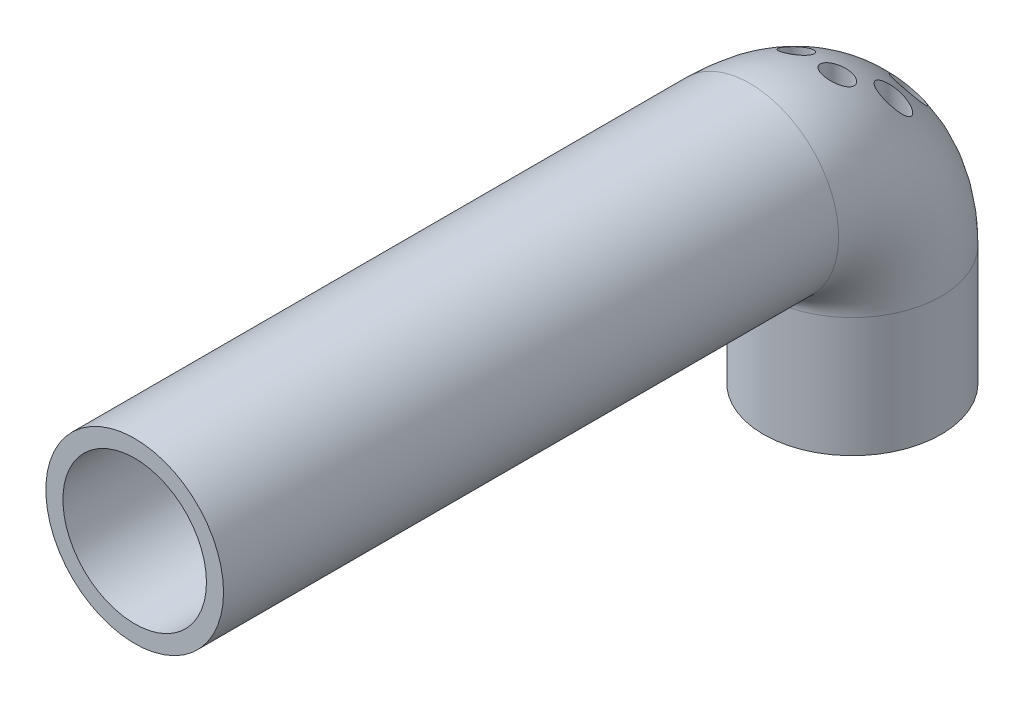
SolidWorks part; units mm, degrees
ref_plane "Front Plane" through (0, 0, 0) normal (0, 0, 1) x (1, 0, 0)
ref_plane "Top Plane" through (0, 0, 0) normal (0, 1, 0) x (1, 0, 0)
ref_plane "Right Plane" through (0, 0, 0) normal (1, 0, 0) x (0, 0, -1)
sketch "Sketch1" plane through (0, 0, 0) normal (0, 1, 0) x (1, 0, 0)
  line L0 (-21.2616, 0) -> (18.5116, 0) construction
  circle A1 centre (0, 0) radius 26
  dimension "D1" = 52
extrude "Boss-Extrude1" add sketch "Sketch1" along normal blind 5
sketch "Sketch8" plane through (0, 5, 0) normal (0, 1, 0) x (1, 0, 0)
  line L0 (6, 10.3923) -> (-6, -10.3923) construction
  line L2 (6, -10.3923) -> (-6, 10.3923) construction
  line L5 (0, 0) -> (0, 12) construction
  circle A0 centre (0, 0) radius 12 construction
  point P4 (-12, 0)
  point P6 (12, 0)
  point P9 (6, 10.3923)
  point P10 (-6, -10.3923)
  point P13 (6, -10.3923)
  point P14 (-6, 10.3923)
  dimension "D1" = 24
  dimension "D2" = 30
  dimension "D3" = 30
hole_wizard "CSK for M4 Flat Head Machine Screw2" positions "Sketch8" profile "Sketch9" countersink size "M4" standard "ANSI Metric" end condition through all
sketch "Sketch9" plane through (-6, 5, -10.3923) normal (1, 0, 0) x (0, 0, 1)
  line L0 (0, 0) -> (0, 5)
  line L1 (0, 5) -> (2.25, 5)
  line L2 (2.25, 5) -> (2.25, 1.75)
  line L3 (2.25, 1.75) -> (4, 0)
  line L5 (4, 0) -> (0, 0)
  line L6 (-2.25, 1.75) -> (-4, 0) construction
  line L11 (0, -6.35) -> (0, 107.95) construction
  dimension "Thru Hole Dia." = 4.5
  dimension "Thru Hole Depth" = 5
  dimension "Near C'Sink Dia." = 8
  dimension "Near C'Sink Angle" = 90
sketch "Sketch10" plane through (0, 0, 0) normal (1, 0, 0) x (0, 0, -1)
  line L0 (0, 5) -> (0, 35)
  line L1 (26, 5) -> (-26, 5) construction
  line L2 (-60, 65) -> (-30, 65)
  arc A0 (-30, 65) -> (0, 35) centre (-30, 35) cw
  dimension "D1" = 30
  dimension "D2" = 30
  dimension "D3" = 30
  dimension "D4" = 30
sketch "Sketch11" plane through (0, 5, 0) normal (0, 1, 0) x (1, 0, 0)
  circle A0 centre (0, 0) radius 21
  circle A1 centre (0, 0) radius 26
  circle A2 centre (0, 0) radius 26
  dimension "D1" = 0
  dimension "D2" = 5
sweep "Sweep3" add profiles "Sketch11" path "Sketch10"
ref_plane "Plane1" through (0, 39, 0) normal (0, -1, 0) x (-1, 0, 0)
sketch "Sketch13" plane through (0, 39, 0) normal (0, -1, 0) x (-1, 0, 0)
  circle A0 centre (-6, 10.3923) radius 2.25 construction
  circle A1 centre (-6, 10.3923) radius 2.25 construction
  circle A2 centre (6, 10.3923) radius 2.25 construction
  circle A3 centre (6, 10.3923) radius 2.25 construction
  circle A4 centre (12, 0) radius 2.25 construction
  circle A5 centre (12, 0) radius 2.25 construction
  circle A6 centre (6, -10.3923) radius 2.25 construction
  circle A7 centre (6, -10.3923) radius 2.25 construction
  circle A8 centre (-6, -10.3923) radius 2.25 construction
  circle A9 centre (-6, -10.3923) radius 2.25 construction
  circle A10 centre (-12, 0) radius 2.25 construction
  circle A11 centre (-12, 0) radius 2.25 construction
  circle A12 centre (6, 10.3923) radius 4
  circle A13 centre (-6, 10.3923) radius 4
  circle A14 centre (-12, 0) radius 4
  circle A15 centre (-6, -10.3923) radius 4
  circle A16 centre (6, -10.3923) radius 4
  circle A17 centre (12, 0) radius 4
  dimension "D1" = 8
extrude "Cut-Extrude1" cut sketch "Sketch13" against normal blind 100
sketch "Sketch14" plane through (0, 0, 0) normal (0, -1, 0) x (1, 0, 0)
  line L0 (0, 0) -> (0, 8.85) construction
  line L1 (0, 0) -> (-7.6643, -4.425) construction
  line L2 (0, 0) -> (7.6643, -4.425) construction
  circle A0 centre (0, 8.85) radius 2.9
  circle A1 centre (0, 0) radius 8.85 construction
  circle A2 centre (7.6643, -4.425) radius 2.9
  circle A3 centre (-7.6643, -4.425) radius 2.9
  dimension "D1" = 17.7
  dimension "D4" = 5.8
  dimension "D2" = 120
  dimension "D3" = 120
extrude "Cut-Extrude2" cut sketch "Sketch14" against normal blind 1
sketch "Sketch15" plane through (0, 0, 60) normal (0, 0, 1) x (1, 0, 0)
  circle A0 centre (0, 65) radius 21 construction
  circle A1 centre (0, 65) radius 26
  circle A2 centre (0, 65) radius 26
  circle A3 centre (0, 65) radius 21
  dimension "D1" = 0
extrude "Boss-Extrude2" add sketch "Sketch15" along normal blind 150
